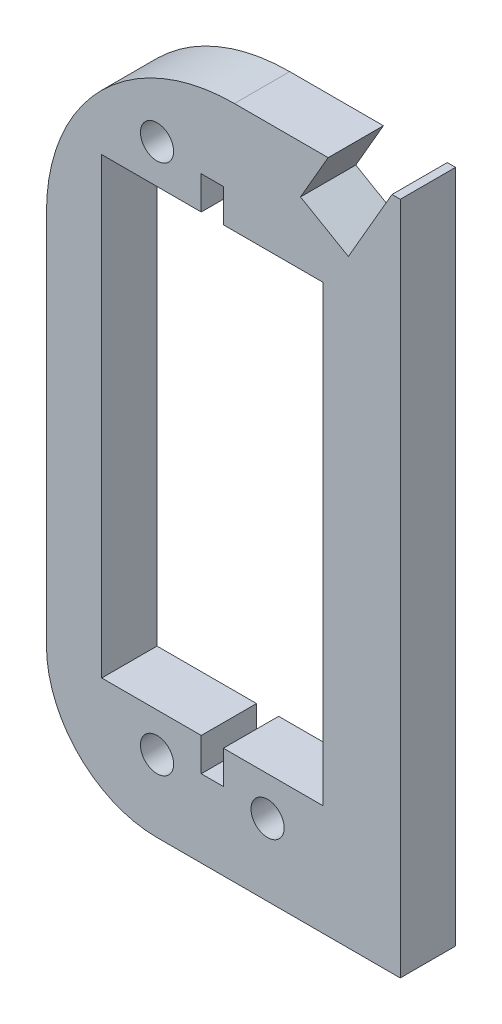
SolidWorks part; units mm, degrees
ref_plane "Plan de face" through (0, 0, 0) normal (0, 0, 1) x (1, 0, 0)
ref_plane "Plan de dessus" through (0, 0, 0) normal (0, 1, 0) x (1, 0, 0)
ref_plane "Plan de droite" through (0, 0, 0) normal (1, 0, 0) x (0, 0, -1)
sketch "Esquisse1" plane through (0, 0, 0) normal (0, 0, 1) x (1, 0, 0)
  line L0 (15, 10) -> (15, 51) construction
  line L1 (0, 0) -> (25, 0)
  line L2 (0, 0) -> (0, 61)
  line L3 (0, 61) -> (15, 61)
  line L4 (31.2508, 61) -> (27.3074, 54.1699)
  line L5 (14, 51) -> (5, 51)
  line L6 (15, 61) -> (25.4773, 61)
  line L7 (25, 10) -> (16, 10)
  line L8 (5, 51) -> (5, 10)
  line L9 (5, 30.5) -> (25, 30.5) construction
  line L10 (25, 10) -> (25, 51)
  line L11 (25, 51) -> (16, 51)
  line L12 (25, 0) -> (32, 0)
  line L13 (32, 0) -> (32, 61)
  line L14 (31.0278, 60.6138) -> (27.2778, 54.1186) construction
  line L15 (27.3074, 54.1699) -> (22.9773, 56.6699)
  line L16 (22.9773, 56.6699) -> (25.4773, 61)
  line L17 (31.2508, 61) -> (32, 61)
  line L18 (16, 10) -> (16, 7)
  line L19 (14, 10) -> (5, 10)
  line L20 (14, 51) -> (14, 54)
  line L21 (14, 54) -> (16, 54)
  line L22 (16, 51) -> (16, 54)
  line L23 (14, 7) -> (16, 7)
  line L24 (14, 10) -> (14, 7)
  circle A0 centre (10, 54.5) radius 1.5
  circle A1 centre (20, 54.5) radius 1.5 construction
  circle A2 centre (20, 6.5) radius 1.5
  circle A3 centre (10, 6.5) radius 1.5
  dimension "D6" = 3.5
  dimension "D8" = 3
  dimension "D1" = 20
  dimension "D2" = 41
  dimension "D3" = 10
  dimension "D4" = 10
  dimension "D5" = 5
  dimension "D7" = 5
  dimension "D9" = 7
  dimension "D10" = 5
  dimension "D11" = 5
  dimension "D12" = 2
  dimension "D13" = 3
extrude "Boss.-Extru.1" add sketch "Esquisse1" along normal blind 5
fillet "Congé1" radius 17 1 edges at (0, 61, 2.5)
fillet "Congé2" radius 10 1 edges at (0, 0, 2.5)
